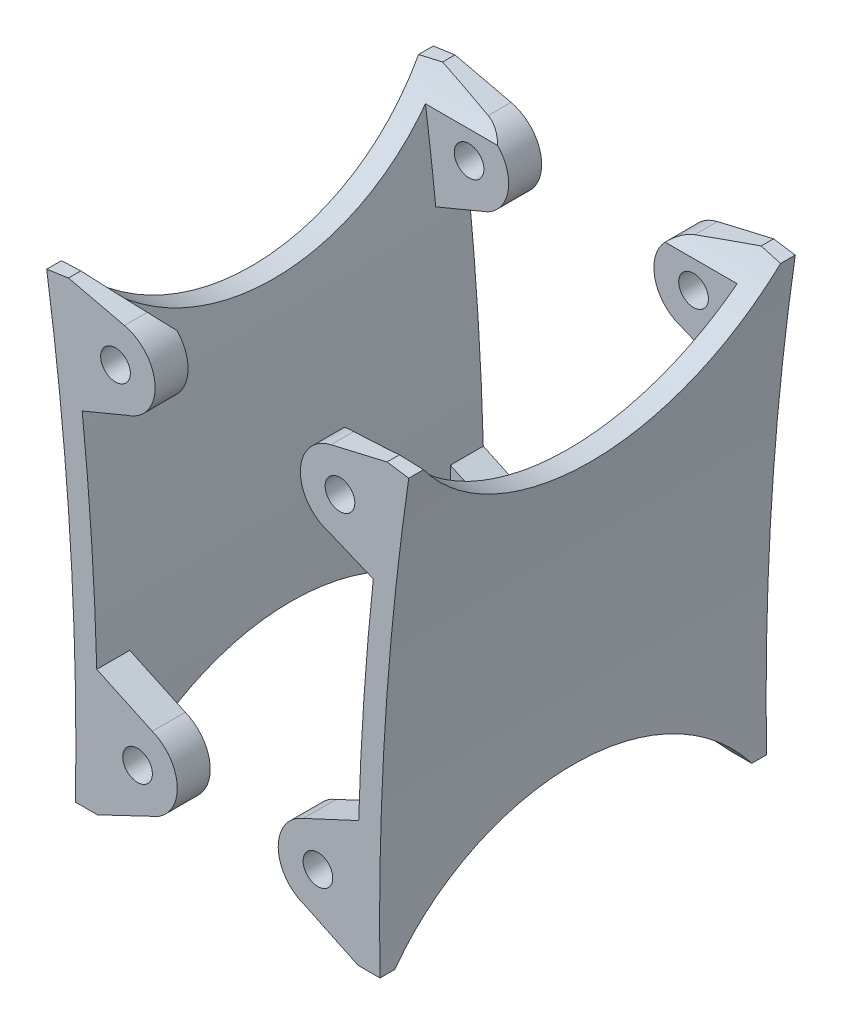
SolidWorks part; units mm, degrees
ref_plane "Front Plane" through (0, 0, 0) normal (0, 0, 1) x (1, 0, 0)
ref_plane "Top Plane" through (0, 0, 0) normal (0, 1, 0) x (1, 0, 0)
ref_plane "Right Plane" through (0, 0, 0) normal (1, 0, 0) x (0, 0, -1)
sketch "Sketch1" plane through (0, 0, 0) normal (0, 0, 1) x (1, 0, 0)
  line L0 (19.5, -32.5864) -> (19.5, -44.6945)
  line L1 (52.4593, -24.8454) -> (48.5018, -24.2638)
  line L2 (47.2228, -106.2713) -> (43.2222, -106.2713)
  line L3 (-8.2228, -106.2713) -> (-4.2222, -106.2713)
  line L4 (-13.4593, -24.8454) -> (-9.5018, -24.2638)
  arc A2 (52.4593, -24.8454) -> (47.2228, -106.2713) centre (547.1466, -97.5401) ccw
  arc A3 (-13.4593, -24.8454) -> (-8.2228, -106.2713) centre (-508.1466, -97.5401) cw
  arc A8 (48.5018, -24.2638) -> (43.2222, -106.2713) centre (547.1466, -97.5401) ccw
  arc A9 (-9.5018, -24.2638) -> (-4.2222, -106.2713) centre (-508.1466, -97.5401) cw
extrude "Boss-Extrude1" add sketch "Sketch1" along normal up to surface (70.3727 mm away) contours L1 A8 L2 A2 | A9 L4 A3 L3
sketch "Sketch3" plane through (0, 0, 0) normal (0, 0, 1) x (1, 0, 0)
  line L0 (48.5018, -24.2638) -> (38.2924, -26.65)
  line L1 (46.0009, -43.9771) -> (36.4777, -40.0129)
  line L2 (43.3453, -83.3876) -> (32.8727, -88.2539)
  line L3 (43.2222, -106.2713) -> (32.8265, -101.3512)
  line L5 (43.3453, -83.3876) -> (43.2222, -106.2713)
  line L6 (46.0009, -43.9771) -> (46.5883, -44.2782)
  line L7 (46.5883, -44.2782) -> (48.5018, -24.2638)
  line L8 (-7.5883, -44.2782) -> (-9.5018, -24.2638)
  line L9 (-7.0009, -43.9771) -> (-7.5883, -44.2782)
  line L10 (-4.3453, -83.3876) -> (-4.2222, -106.2713)
  line L11 (-4.2222, -106.2713) -> (6.1735, -101.3512)
  line L12 (-4.3453, -83.3876) -> (6.1273, -88.2539)
  line L13 (-7.0009, -43.9771) -> (2.5223, -40.0129)
  line L14 (-9.5018, -24.2638) -> (0.7076, -26.65)
  circle A0 centre (39.9349, -33.6777) radius 2.7
  circle A1 centre (35.9208, -94.8134) radius 2.7
  arc A2 (38.2924, -26.65) -> (37.8756, -40.5948) centre (39.9349, -33.6777) ccw
  arc A3 (32.8727, -88.2539) -> (32.8265, -101.3512) centre (35.9208, -94.8134) ccw
  arc A4 (48.5018, -24.2638) -> (43.2222, -106.2713) centre (547.1466, -97.5401) ccw construction
  arc A6 (6.1273, -88.2539) -> (6.1735, -101.3512) centre (3.0792, -94.8134) cw
  arc A7 (0.7076, -26.65) -> (1.1244, -40.5948) centre (-0.9349, -33.6777) cw
  circle A8 centre (3.0792, -94.8134) radius 2.7
  circle A9 centre (-0.9349, -33.6777) radius 2.7
extrude "Boss-Extrude3" add sketch "Sketch3" along normal blind 6 contours L0 A2 L1 L6 L7 A0 | L2 A3 L3 L5 A1 | A6 L12 L10 L11 A8 | A7 L14 L8 L9 L13 A9
sketch "Sketch4" plane through (0, 0, 70.3727) normal (0, 0, -1) x (-1, 0, 0)
  line L0 (4.2222, -106.2713) -> (-5.5418, -101.6144)
  line L1 (4.3453, -83.3876) -> (-5.7716, -88.1001)
  line L2 (7.0009, -43.9771) -> (-1.1244, -40.5948)
  line L3 (7.0009, -43.9771) -> (-2.5223, -40.0129) construction
  line L4 (9.5018, -24.2638) -> (-0.7076, -26.65)
  line L5 (9.5018, -24.2638) -> (-0.7076, -26.65) construction
  line L6 (4.2222, -106.2713) -> (5.8047, -106.2713)
  line L7 (8.2228, -106.2713) -> (4.2222, -106.2713) construction
  line L8 (5.8047, -106.2713) -> (5.8047, -83.3876)
  line L9 (5.8047, -83.3876) -> (4.3453, -83.3876)
  line L10 (7.0009, -43.9771) -> (8.7655, -43.9771)
  line L11 (8.7655, -43.9771) -> (10.9861, -25.2657)
  line L12 (10.9861, -25.2657) -> (9.5018, -24.2638)
  line L13 (-19.5, -105.9443) -> (-19.5, -91.9609)
  line L14 (-49.9861, -25.2657) -> (-48.5018, -24.2638)
  line L15 (-47.7655, -43.9771) -> (-49.9861, -25.2657)
  line L16 (-46.0009, -43.9771) -> (-47.7655, -43.9771)
  line L17 (-44.8047, -83.3876) -> (-43.3453, -83.3876)
  line L18 (-44.8047, -106.2713) -> (-44.8047, -83.3876)
  line L19 (-43.2222, -106.2713) -> (-44.8047, -106.2713)
  line L20 (-48.5018, -24.2638) -> (-38.2924, -26.65)
  line L21 (-46.0009, -43.9771) -> (-37.8756, -40.5948)
  line L22 (-43.3453, -83.3876) -> (-33.2284, -88.1001)
  line L23 (-43.2222, -106.2713) -> (-33.4582, -101.6144)
  circle A4 centre (0.9349, -33.6777) radius 2.7
  arc A5 (-0.7076, -26.65) -> (-1.1244, -40.5948) centre (0.9349, -33.6777) ccw
  circle A6 centre (-3.0792, -94.8134) radius 2.7
  arc A7 (-5.7716, -88.1001) -> (-5.5418, -101.6144) centre (-3.0792, -94.8134) ccw
  arc A8 (-27.11, -98.0751) -> (-11.89, -98.0751) centre (-19.5, -98.33) ccw construction
  arc A9 (-33.2284, -88.1001) -> (-33.4582, -101.6144) centre (-35.9208, -94.8134) cw
  circle A10 centre (-35.9208, -94.8134) radius 2.7
  arc A11 (-38.2924, -26.65) -> (-37.8756, -40.5948) centre (-39.9349, -33.6777) cw
  circle A12 centre (-39.9349, -33.6777) radius 2.7
extrude "Boss-Extrude4" add sketch "Sketch4" along normal blind 6 contours A9 L22 L17 L18 L19 L23 A10 | A11 L20 L14 L15 L16 L21 A12 | L1 A7 L0 L6 L8 L9 A6 | L4 A5 L2 L10 L11 L12 A4
sketch "Sketch5" plane through (42, 0, 0) normal (1, 0, 0) x (0, 0, -1)
  line L0 (-1.0852, -22.5937) -> (-69.2874, -22.5937)
  line L1 (-35.1863, -24.8454) -> (-35.1863, 0)
  line L2 (-70.3727, -24.8454) -> (0, -24.8454) construction
  line L3 (-2.6891, -24.8454) -> (-67.6835, -24.8454)
  line L4 (0, -65.5584) -> (-14.0028, -65.5584)
  line L5 (0, -106.2713) -> (0, -24.8454) construction
  line L6 (-2.6891, -106.2713) -> (-67.6835, -106.2713)
  line L7 (-35.1863, -106.2713) -> (-35.1863, -131.1167)
  line L8 (-1.0852, -108.523) -> (-69.2874, -108.523)
  arc A0 (-69.2874, -22.5937) -> (-1.0852, -22.5937) centre (-35.1863, 0) ccw
  arc A1 (-69.2874, -108.523) -> (-1.0852, -108.523) centre (-35.1863, -131.1167) cw
extrude "Cut-Extrude1" cut sketch "Sketch5" along normal blind 37 and the other way blind 122 contours L3 A0 | L3 A0 L0 L1 | L0 A0 L3 L1 | A1 L6 | A1 L6 L7 L8 | A1 L8 L7 L6
